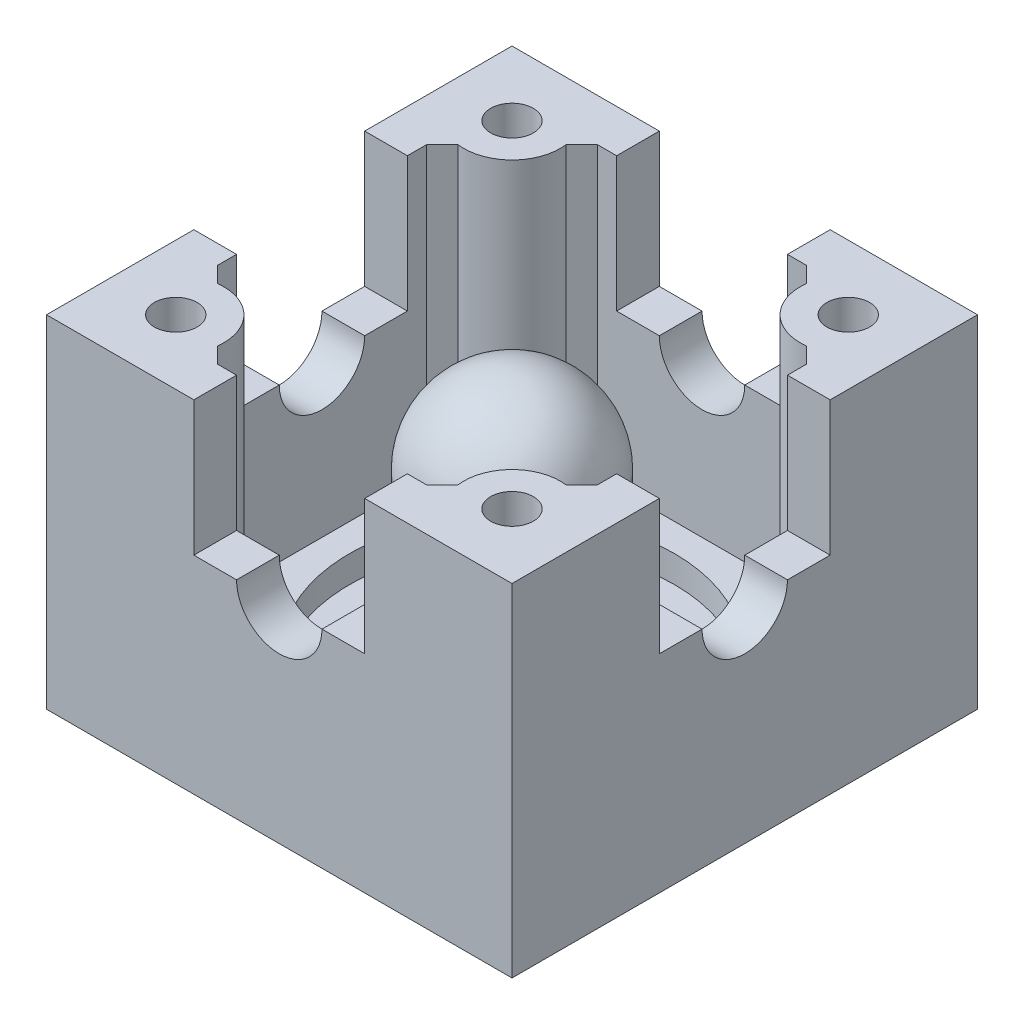
SolidWorks part; units mm, degrees
ref_plane "Front Plane" through (0, 0, 0) normal (0, 0, 1) x (1, 0, 0)
ref_plane "Top Plane" through (0, 0, 0) normal (0, 1, 0) x (1, 0, 0)
ref_plane "Right Plane" through (0, 0, 0) normal (1, 0, 0) x (0, 0, -1)
sketch "Sketch1" plane through (0, 0, 0) normal (0, 1, 0) x (1, 0, 0)
  line L1 (0, 0) -> (13.843, 0)
  line L2 (0, 0) -> (0, 13.843)
  line L3 (0, 13.843) -> (13.843, 13.843)
  line L4 (13.843, 0) -> (13.843, 13.843)
  dimension "D1" = 13.843
  dimension "D2" = 13.843
extrude "main body extrude" add sketch "Sketch1" along normal blind 10.16
sketch "Sketch4" plane through (0, 10.16, 0) normal (0, 1, 0) x (1, 0, 0)
  line L0 (0, 13.843) -> (13.843, 0) construction
  line L1 (13.843, 0) -> (13.843, 13.843) construction
  line L2 (1.27, 10.033) -> (3.81, 12.573)
  line L7 (13.843, 13.843) -> (0, 13.843) construction
  line L8 (3.81, 1.27) -> (10.033, 1.27)
  line L9 (10.033, 12.573) -> (12.573, 10.033)
  line L10 (0, 0) -> (13.843, 0) construction
  line L15 (1.27, 3.81) -> (1.27, 10.033)
  line L16 (3.81, 12.573) -> (10.033, 12.573)
  line L17 (12.573, 3.81) -> (12.573, 10.033)
  line L18 (1.27, 1.27) -> (12.573, 12.573) construction
  line L19 (1.27, 12.573) -> (12.573, 1.27) construction
  line L20 (10.033, 1.27) -> (12.573, 3.81)
  line L21 (1.27, 3.81) -> (3.81, 1.27)
  circle A0 centre (1.9215, 11.9215) radius 0.635
  circle A1 centre (11.9215, 11.9215) radius 0.635
  circle A2 centre (11.9215, 1.9215) radius 0.635
  circle A3 centre (1.9215, 1.9215) radius 0.635
  circle A4 centre (1.9215, 11.9215) radius 1.435
  circle A5 centre (11.9215, 11.9215) radius 1.435
  circle A6 centre (11.9215, 1.9215) radius 1.435
  circle A7 centre (1.9215, 1.9215) radius 1.435
  point P5 (6.9215, 6.9215)
  point P6 (6.9215, 6.9215)
  point P27 (6.9215, 6.9215)
  point P28 (6.9215, 6.9215)
  point P44 (6.9215, 6.9215)
  dimension "D3" = 1.27
  dimension "D6" = 0.8
  dimension "D1" = 1.27
  dimension "D2" = 1.27
  dimension "D5" = 10
  dimension "D4" = 4
  dimension "D7" = 4
extrude "main body cut" cut sketch "Sketch4" against normal offset from surface (9.36 mm away) 0.8
sketch "Sketch21" plane through (0, 10.16, 0) normal (0, 1, 0) x (1, 0, 0)
  line L0 (0, 13.843) -> (13.843, 0) construction
  circle A0 centre (1.9215, 11.9215) radius 0.635
  circle A1 centre (11.9215, 11.9215) radius 0.635
  circle A2 centre (11.9215, 1.9215) radius 0.635
  circle A3 centre (1.9215, 1.9215) radius 0.635
  point P7 (6.9215, 6.9215)
  point P17 (6.9215, 6.9215)
  dimension "D2" = 1.27
  dimension "D1" = 4
extrude "screw holes cut" cut sketch "Sketch21" against normal through all
sketch "Sketch5" plane through (0, 0, 0) normal (0, 0, 1) x (1, 0, 0)
  line L0 (6.9215, 12.7116) -> (6.9215, 6.1595) construction
  line L1 (8.1915, 12.7116) -> (8.1915, 6.1595)
  line L2 (0, 10.16) -> (13.843, 10.16) construction
  line L3 (5.6515, 12.7116) -> (5.6515, 6.1595)
  line L4 (6.9215, 6.1595) -> (6.9215, 2.6781) construction
  line L5 (4.3815, 12.7116) -> (9.4615, 12.7116)
  line L6 (4.3815, 12.7116) -> (4.3815, 6.1595)
  line L7 (4.3815, 6.1595) -> (9.4615, 6.1595)
  line L8 (9.4615, 12.7116) -> (9.4615, 6.1595)
  line L9 (4.3815, 12.7116) -> (9.4615, 6.1595) construction
  line L10 (4.3815, 6.1595) -> (9.4615, 12.7116) construction
  line L19 (11.811, 5.207) -> (10.541, 5.207)
  line L20 (2.032, 8.509) -> (3.302, 8.509)
  line L21 (2.032, 8.509) -> (2.032, 5.207)
  line L22 (2.032, 5.207) -> (3.302, 5.207)
  line L23 (3.302, 8.509) -> (3.302, 5.207)
  line L24 (10.541, 8.509) -> (10.541, 5.207)
  line L25 (11.811, 8.509) -> (10.541, 8.509)
  line L26 (11.811, 8.509) -> (11.811, 5.207)
  arc A1 (8.1915, 12.7116) -> (5.6515, 12.7116) centre (6.9215, 12.7116) ccw
  arc A2 (5.6515, 6.1595) -> (8.1915, 6.1595) centre (6.9215, 6.1595) ccw
  circle A3 centre (6.9215, 6.1595) radius 1.27 construction
  point P2 (6.9215, 10.16)
  point P3 (6.9215, 9.4356)
  point P14 (6.9215, 9.4356)
  dimension "D1" = 2.54
  dimension "D2" = 4.0005
  dimension "D3" = 5.08
  dimension "D4" = 1.27
  dimension "D5" = 3.302
  dimension "D6" = 7.239
  dimension "D7" = 1.651
extrude "x axis slot" cut sketch "Sketch5" against normal through all
sketch "Sketch6" plane through (13.843, 0, 0) normal (1, 0, 0) x (0, 0, -1)
  line L0 (0, 10.16) -> (13.843, 10.16) construction
  line L1 (6.9215, 6.1595) -> (6.9215, 12.6452) construction
  line L2 (5.6515, 6.1595) -> (5.6515, 12.6452)
  line L3 (8.1915, 6.1595) -> (8.1915, 12.6452)
  line L4 (6.9215, 6.1595) -> (6.9215, 2.9038) construction
  line L5 (4.3815, 12.6452) -> (9.4615, 12.6452)
  line L6 (4.3815, 12.6452) -> (4.3815, 6.1595)
  line L7 (4.3815, 6.1595) -> (9.4615, 6.1595)
  line L8 (9.4615, 12.6452) -> (9.4615, 6.1595)
  line L9 (4.3815, 12.6452) -> (9.4615, 6.1595) construction
  line L10 (4.3815, 6.1595) -> (9.4615, 12.6452) construction
  circle A0 centre (6.9215, 6.1595) radius 1.27 construction
  arc A1 (5.6515, 6.1595) -> (8.1915, 6.1595) centre (6.9215, 6.1595) ccw
  arc A2 (8.1915, 12.6452) -> (5.6515, 12.6452) centre (6.9215, 12.6452) ccw
  point P6 (6.9215, 10.16)
  point P7 (6.9215, 9.4024)
  point P13 (6.9215, 7.4295)
  point P15 (6.9215, 9.4024)
  dimension "D1" = 2.54
  dimension "D2" = 4.0005
  dimension "D3" = 5.08
extrude "y axis slot" cut sketch "Sketch6" against normal through all
sketch "Sketch11" plane through (0, 0.8, 0) normal (0, 1, 0) x (1, 0, 0)
  line L0 (1.27, 12.573) -> (12.573, 1.27) construction
  line L1 (12.573, 12.573) -> (1.27, 1.27) construction
  line L3 (1.27, 12.573) -> (12.573, 12.573)
  line L4 (1.27, 12.573) -> (1.27, 1.27)
  line L5 (1.27, 1.27) -> (12.573, 1.27)
  line L6 (12.573, 12.573) -> (12.573, 1.27)
  line L9 (3.81, 12.573) -> (4.3815, 12.573) construction
  line L10 (1.27, 9.4615) -> (1.27, 10.033) construction
  line L12 (3.81, 1.27) -> (4.3815, 1.27) construction
  circle A0 centre (6.9215, 6.9215) radius 4.826
  circle A1 centre (1.9215, 11.9215) radius 0.635
  circle A2 centre (11.9215, 11.9215) radius 0.635
  circle A3 centre (11.9215, 1.9215) radius 0.635
  circle A4 centre (1.9215, 1.9215) radius 0.635
  dimension "D1" = 9.652
extrude "spring retainer extrude" add sketch "Sketch11" along normal blind 0.8
sketch "Sketch12" plane through (0, 0.8, 0) normal (0, 1, 0) x (1, 0, 0)
  line L0 (0, 13.843) -> (13.843, 0) construction
  circle A0 centre (6.9215, 6.9215) radius 2.54
  dimension "D1" = 5.08
extrude "Stick support" add sketch "Sketch12" along normal up to vertex (1.359 mm away)
sketch "Sketch20" plane through (0, 6.1595, 0) normal (0, 1, 0) x (1, 0, 0)
  circle A0 centre (6.9215, 6.9215) radius 2.54
  circle A1 centre (6.9215, 6.9215) radius 2.54 construction
extrude "Boss-Extrude9" add sketch "Sketch20" along normal blind 2.54
fillet "Fillet4" radius 2.54 1 edges at (6.9215, 8.6995, -4.3815)
sketch "Sketch16" [suppressed] plane through (0, 10.16, 0) normal (0, 1, 0) x (1, 0, 0)
  line L0 (1.2, 10.103) -> (3.74, 12.643)
  line L1 (1.2, 12.643) -> (1.2, 1.2) construction
  line L2 (12.643, 12.643) -> (1.2, 12.643) construction
  line L3 (1.2, 10.103) -> (1.2, 12.643)
  line L4 (1.2, 12.643) -> (3.74, 12.643)
  line L5 (0, 13.843) -> (13.843, 0) construction
  line L6 (10.103, 12.643) -> (12.643, 10.103)
  line L7 (12.643, 12.643) -> (12.643, 10.103)
  line L8 (10.103, 12.643) -> (12.643, 12.643)
  line L9 (12.643, 3.74) -> (10.103, 1.2)
  line L10 (12.643, 1.2) -> (10.103, 1.2)
  line L11 (12.643, 3.74) -> (12.643, 1.2)
  line L12 (3.74, 1.2) -> (1.2, 3.74)
  line L13 (1.2, 1.2) -> (1.2, 3.74)
  line L14 (3.74, 1.2) -> (1.2, 1.2)
  point P12 (6.9215, 6.9215)
  point P25 (6.9215, 6.9215)
  dimension "D1" = 2.54
  dimension "D2" = 2.54
  dimension "D3" = 4
extrude "screw extrude 1" [suppressed] add sketch "Sketch16" against normal up to surface (8.56 mm away)
sketch "Sketch15" [suppressed] plane through (0, 10.16, 0) normal (0, 1, 0) x (1, 0, 0)
  line L0 (0, 13.843) -> (13.843, 0) construction
  circle A0 centre (1.9215, 11.9215) radius 0.635
  circle A1 centre (11.9215, 11.9215) radius 0.635
  circle A2 centre (11.9215, 1.9215) radius 0.635
  circle A3 centre (1.9215, 1.9215) radius 0.635
  point P4 (6.9215, 6.9215)
  point P16 (6.9215, 6.9215)
  dimension "D1" = 1.27
  dimension "D3" = 10
  dimension "D2" = 4
extrude "screw cut 2" [suppressed] cut sketch "Sketch15" against normal through all
sketch "Sketch17" [suppressed] plane through (0, 10.16, 0) normal (0, 1, 0) x (1, 0, 0)
  line L0 (0, 13.843) -> (13.843, 0) construction
  circle A0 centre (1.9215, 11.9215) radius 1.143
  circle A1 centre (11.9215, 11.9215) radius 1.143
  circle A2 centre (11.9215, 1.9215) radius 1.143
  circle A3 centre (1.9215, 1.9215) radius 1.143
  circle A4 centre (1.9215, 11.9215) radius 0.635 construction
  circle A5 centre (1.9215, 11.9215) radius 0.635
  circle A6 centre (11.9215, 11.9215) radius 0.635
  circle A7 centre (11.9215, 1.9215) radius 0.635
  circle A8 centre (1.9215, 1.9215) radius 0.635
  point P7 (6.9215, 6.9215)
  point P17 (6.9215, 6.9215)
  point P27 (6.9215, 6.9215)
  dimension "D2" = 0.508
  dimension "D1" = 4
  dimension "D3" = 4
extrude "screw extrude 2" [suppressed] add sketch "Sketch17" against normal up to surface (8.56 mm away)
sketch "Sketch9" plane through (0, 0, 0) normal (0, -1, 0) x (1, 0, 0)
  line L0 (6.9215, 0) -> (6.9215, -13.843) construction
  line L1 (0, 0) -> (13.843, 0) construction
  line L2 (13.843, -13.843) -> (0, -13.843) construction
  line L3 (0, -6.9215) -> (13.843, -6.9215) construction
  line L4 (0, -13.843) -> (0, 0) construction
  line L5 (13.843, 0) -> (13.843, -13.843) construction
  circle A0 centre (6.9215, -1.8415) radius 0.625
  circle A1 centre (6.9215, -12.0015) radius 0.625
  dimension "D1" = 1.25
  dimension "D2" = 10.16
extrude "mounting holes 1 cut " [suppressed] cut sketch "Sketch9" against normal blind 2.54
chamfer "Chamfer1" [suppressed] distance 0.635 angle 45
